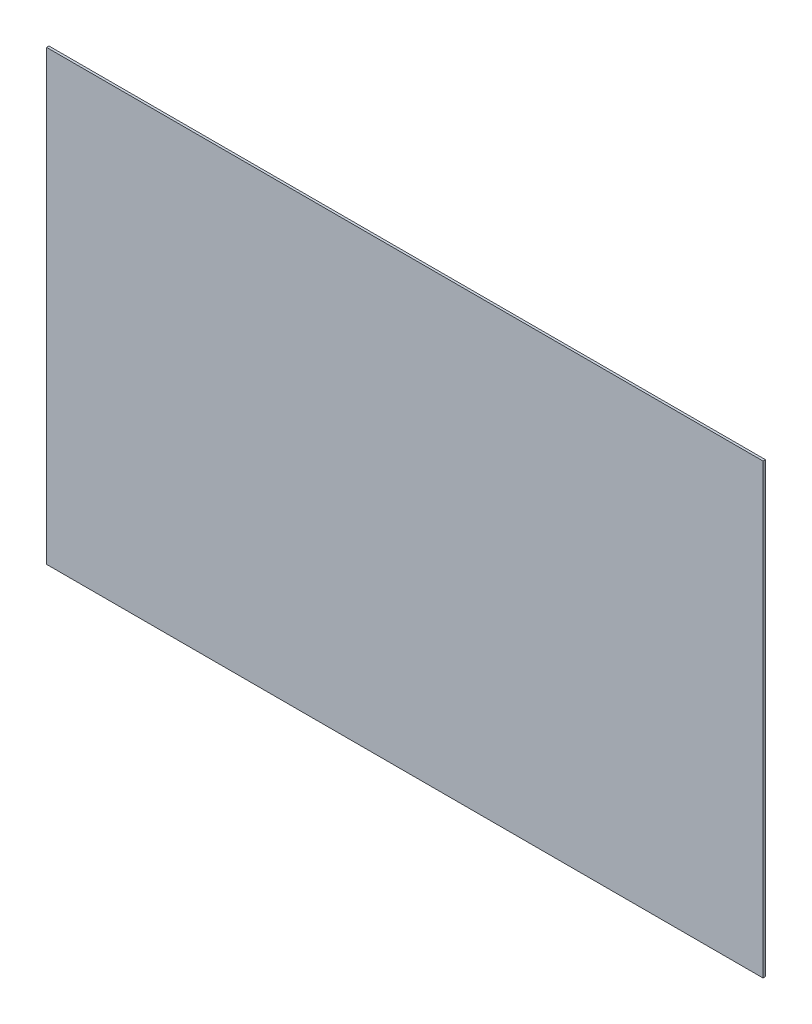
SolidWorks part; units mm, degrees
ref_plane "Front Plane" through (0, 0, 0) normal (0, 0, 1) x (1, 0, 0)
ref_plane "Top Plane" through (0, 0, 0) normal (0, 1, 0) x (1, 0, 0)
ref_plane "Right Plane" through (0, 0, 0) normal (1, 0, 0) x (0, 0, -1)
ref_plane "Back Plane" through (0, 0, -4) normal (0, 0, 1) x (1, 0, 0)
ref_plane "Bottom Plane" through (0, -750, 0) normal (0, 1, 0) x (-1, 0, 0)
ref_plane "Left Plane" through (-1200, 0, 0) normal (1, 0, 0) x (0, 0, -1)
sketch "Sketch1" plane through (0, -750, 0) normal (0, 1, 0) x (-1, 0, 0)
  line L0 (1200, 55) -> (1200, -55) construction
  line L1 (0, 0) -> (1200, 0)
  line L2 (0, 0) -> (0, -4)
  line L3 (0, -4) -> (1200, -4)
  line L4 (1200, 0) -> (1200, -4)
  line L5 (0, 55) -> (0, -55) construction
  line L6 (55, -4) -> (-55, -4) construction
  line L8 (55, 0) -> (-55, 0) construction
extrude "Back Panel" add sketch "Sketch1" along normal up to surface (750 mm away) up to plane "Top Plane"
